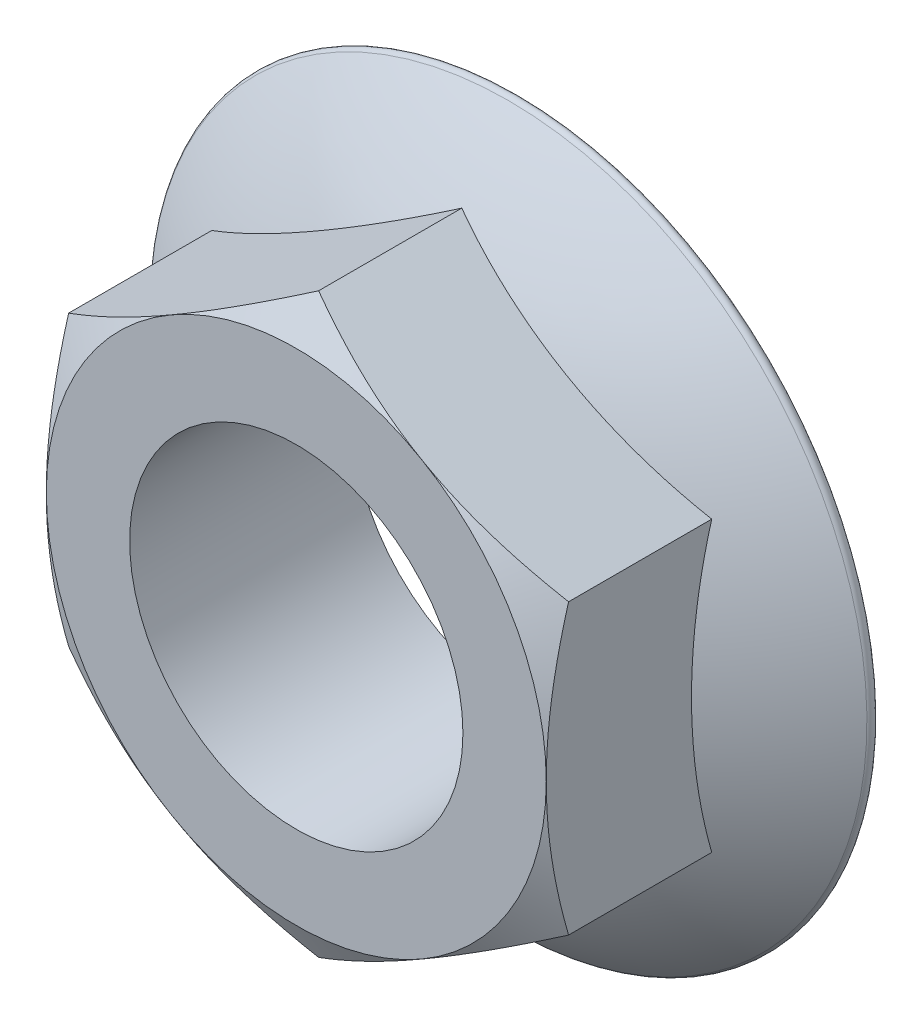
SolidWorks part; units mm, degrees
ref_plane "Front Plane" through (0, 0, 0) normal (0, 0, 1) x (1, 0, 0)
ref_plane "Top Plane" through (0, 0, 0) normal (0, 1, 0) x (1, 0, 0)
ref_plane "Right Plane" through (0, 0, 0) normal (1, 0, 0) x (0, 0, -1)
sketch "Sketch1" plane through (0, 0, 0) normal (0, 0, 1) x (1, 0, 0)
  line L1 (-22.5, 12.9904) -> (-22.5, -12.9904)
  line L2 (-22.5, -12.9904) -> (0, -25.9808)
  line L3 (0, -25.9808) -> (22.5, -12.9904)
  line L4 (22.5, -12.9904) -> (22.5, 12.9904)
  line L5 (22.5, 12.9904) -> (0, 25.9808)
  line L6 (0, 25.9808) -> (-22.5, 12.9904)
  circle A0 centre (0, 0) radius 22.5 construction
  dimension "D1" = 45
extrude "Boss-Extrude1" add sketch "Sketch1" along normal blind 20
sketch "Sketch2" plane through (0, 0, 0) normal (1, 0, 0) x (0, 0, -1)
  line L0 (0, 0) -> (-12, 0)
  line L1 (0, -31.95) -> (0, 0)
  arc A0 (-12, 0) -> (-0.894, -32.2578) centre (40.4001, 0) ccw
  arc A1 (-0.894, -32.2578) -> (0, -31.95) centre (-0.5, -31.95) ccw
  dimension "D2" = 0.5
  dimension "D1" = 12
  dimension "D3" = 31.95
revolve "Revolve1" add sketch "Sketch2" angle 360 about L0
sketch "Sketch3" plane through (0, 0, 20) normal (0, 0, 1) x (1, 0, 0)
  circle A0 centre (0, 0) radius 22.5
extrude "Cut-Extrude1" cut sketch "Sketch3" against normal through all draft 60 flip side to cut
sketch "Sketch4" plane through (0, 0, 20) normal (0, 0, 1) x (1, 0, 0)
  circle A0 centre (0, 0) radius 15
  dimension "D1" = 30
extrude "Cut-Extrude2" cut sketch "Sketch4" against normal through all
cosmetic thread "Cosmetic Thread1" parameters "D2"=31.75
